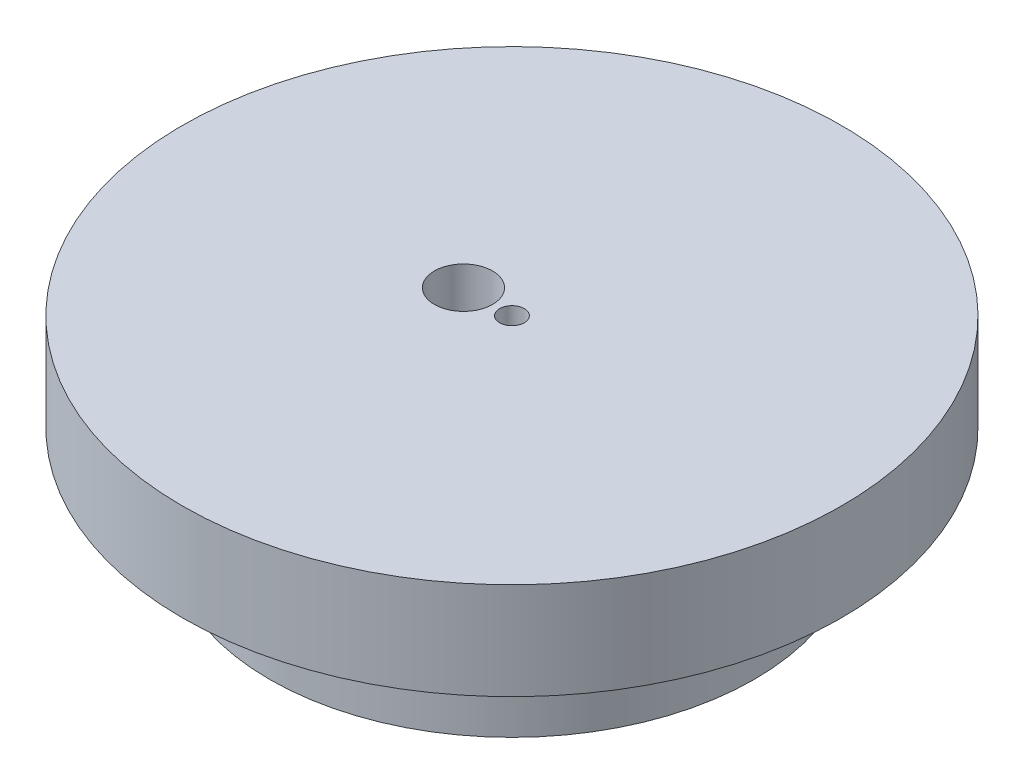
SolidWorks part; units mm, degrees
ref_plane "Front Plane" through (0, 0, 0) normal (0, 0, 1) x (1, 0, 0)
ref_plane "Top Plane" through (0, 0, 0) normal (0, 1, 0) x (1, 0, 0)
ref_plane "Right Plane" through (0, 0, 0) normal (1, 0, 0) x (0, 0, -1)
sketch "Sketch1" plane through (0, 0, 0) normal (0, 1, 0) x (1, 0, 0)
  line L2 (-1.5034, 11.025) -> (1.5034, 11.025)
  line L3 (-1.5034, 11.025) -> (-2.4314, 8.165)
  line L4 (1.5034, 11.025) -> (2.4314, 8.165)
  line L5 (6.7328, 8.8589) -> (4.0542, 7.4928)
  line L6 (6.7328, 8.8589) -> (8.8589, 6.7328)
  line L7 (8.8589, 6.7328) -> (7.4928, 4.0542)
  line L8 (11.025, 1.5034) -> (8.165, 2.4314)
  line L9 (11.025, 1.5034) -> (11.025, -1.5034)
  line L10 (11.025, -1.5034) -> (8.165, -2.4314)
  line L11 (8.8589, -6.7328) -> (7.4928, -4.0542)
  line L64 (8.8589, -6.7328) -> (6.7328, -8.8589)
  line L65 (6.7328, -8.8589) -> (4.0542, -7.4928)
  line L66 (1.5034, -11.025) -> (2.4314, -8.165)
  line L67 (1.5034, -11.025) -> (-1.5034, -11.025)
  line L68 (-1.5034, -11.025) -> (-2.4314, -8.165)
  line L69 (-6.7328, -8.8589) -> (-4.0542, -7.4928)
  line L70 (-6.7328, -8.8589) -> (-8.8589, -6.7328)
  line L71 (-8.8589, -6.7328) -> (-7.4928, -4.0542)
  line L72 (-11.025, -1.5034) -> (-8.165, -2.4314)
  line L73 (-11.025, -1.5034) -> (-11.025, 1.5034)
  line L74 (-11.025, 1.5034) -> (-8.165, 2.4314)
  line L75 (-8.8589, 6.7328) -> (-7.4928, 4.0542)
  line L76 (-8.8589, 6.7328) -> (-6.7328, 8.8589)
  line L77 (-6.7328, 8.8589) -> (-4.0542, 7.4928)
  circle A23 centre (0, 0) radius 25
  circle A26 centre (0, 0) radius 8.5193 construction
  arc A27 (2.4314, 8.165) -> (4.0542, 7.4928) centre (0, 0) cw
  arc A28 (7.4928, 4.0542) -> (8.165, 2.4314) centre (0, 0) cw
  arc A29 (8.165, -2.4314) -> (7.4928, -4.0542) centre (0, 0) cw
  arc A30 (4.0542, -7.4928) -> (2.4314, -8.165) centre (0, 0) cw
  arc A31 (-2.4314, -8.165) -> (-4.0542, -7.4928) centre (0, 0) cw
  arc A32 (-7.4928, -4.0542) -> (-8.165, -2.4314) centre (0, 0) cw
  arc A33 (-8.165, 2.4314) -> (-7.4928, 4.0542) centre (0, 0) cw
  arc A34 (-4.0542, 7.4928) -> (-2.4314, 8.165) centre (0, 0) cw
  point P8 (0, 0)
  point P9 (0, 0)
  point P47 (0, 0)
  dimension "D1" = 50
extrude "Boss-Extrude1" add sketch "Sketch1" along normal blind 10
sketch "Sketch2" plane through (0, 10, 0) normal (0, 1, 0) x (1, 0, 0)
  circle A0 centre (0, 0) radius 1.27
  circle A1 centre (0, 0) radius 34
  dimension "D1" = 2.54
  dimension "D2" = 68
extrude "Boss-Extrude2" add sketch "Sketch2" along normal blind 10
sketch "Sketch3" plane through (0, 20, 0) normal (0, 1, 0) x (1, 0, 0)
  circle A0 centre (-5, 0) radius 3
  dimension "D2" = 6
  dimension "D1" = 5
extrude "Cut-Extrude1" cut sketch "Sketch3" against normal through all
